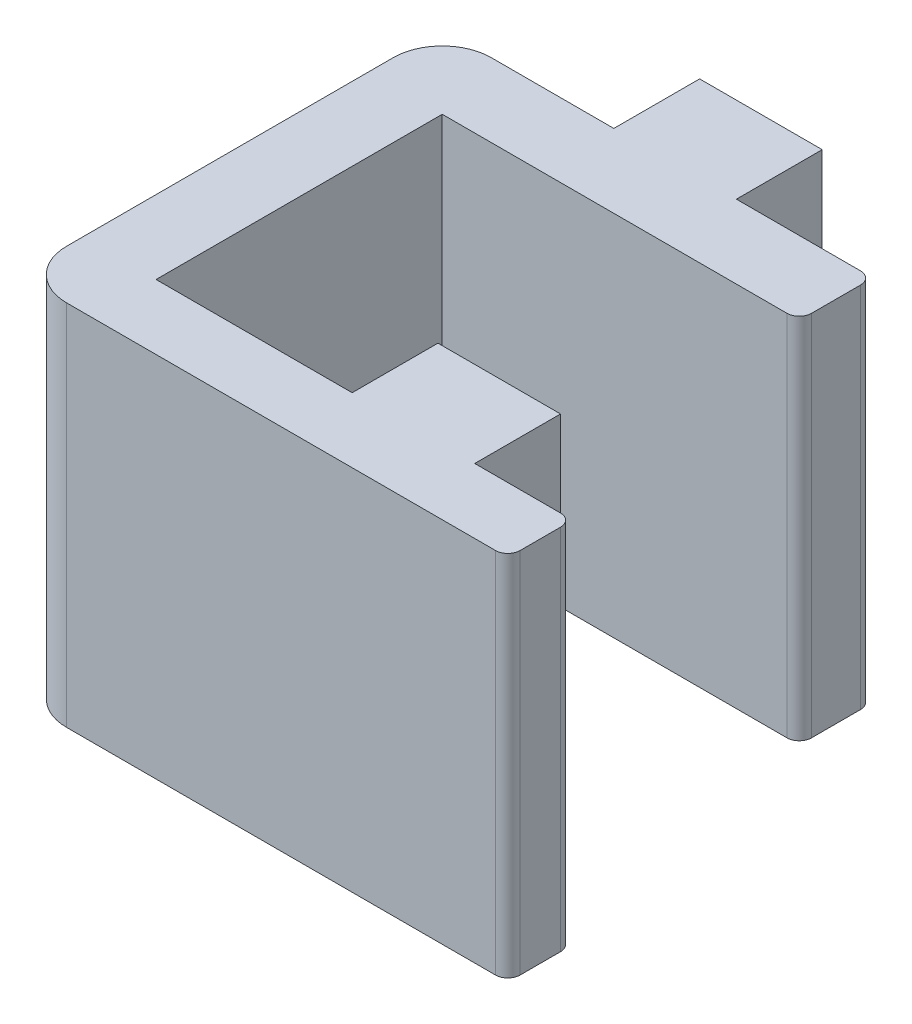
SolidWorks part; units mm, degrees
ref_plane "Front Plane" through (0, 0, 0) normal (0, 0, 1) x (1, 0, 0)
ref_plane "Top Plane" through (0, 0, 0) normal (0, 1, 0) x (1, 0, 0)
ref_plane "Right Plane" through (0, 0, 0) normal (1, 0, 0) x (0, 0, -1)
sketch "Sketch1" plane through (0, 0, 0) normal (0, 1, 0) x (1, 0, 0)
  line L1 (0, 0) -> (-20, 0)
  line L2 (0, 0) -> (0, 2.65)
  line L3 (0, 2.65) -> (-17, 2.65)
  line L6 (-20, 0) -> (-20, 17.325)
  line L8 (-17, 2.65) -> (-17, 14.325)
  line L9 (-20, 17.325) -> (-2.4355, 17.325)
  line L11 (-17, 14.325) -> (-2.4355, 14.325)
  line L12 (-2.4355, 17.325) -> (-2.4355, 14.325)
  dimension "D1" = 2.65
  dimension "D2" = 17.325
  dimension "D3" = 20
  dimension "D4" = 3
  dimension "D5" = 3
extrude "Boss-Extrude1" add sketch "Sketch1" along normal blind 15
sketch "Sketch2" plane through (0, 0, -2.65) normal (0, 0, -1) x (-1, 0, 0)
  line L0 (0, 0) -> (17, 0) construction
  line L1 (9, 0) -> (4, 0)
  line L2 (9, 0) -> (9, 15)
  line L3 (9, 15) -> (4, 15)
  line L4 (4, 0) -> (4, 15)
  line L5 (0, 15) -> (17, 15) construction
  line L6 (17, 15) -> (17, 0) construction
  dimension "D1" = 8
  dimension "D2" = 5
extrude "Boss-Extrude2" add sketch "Sketch2" along normal blind 3.5
sketch "Sketch3" plane through (0, 0, -17.325) normal (0, 0, -1) x (-1, 0, 0)
  line L0 (2.4355, 0) -> (20, 0) construction
  line L1 (13, 0) -> (8, 0)
  line L2 (13, 0) -> (13, 15)
  line L3 (13, 15) -> (8, 15)
  line L4 (8, 0) -> (8, 15)
  line L5 (2.4355, 15) -> (20, 15) construction
  line L6 (20, 15) -> (20, 0) construction
  dimension "D1" = 7
  dimension "D2" = 5
extrude "Boss-Extrude3" add sketch "Sketch3" along normal blind 3.5
fillet "Fillet1" radius 2 2 edges at (-20, 7.5, 0) (-20, 7.5, -17.325)
fillet "Fillet2" radius 0.5 4 edges at (-2.4355, 7.5, -17.325) (-2.4355, 7.5, -14.325) (0, 7.5, 0) (0, 7.5, -2.65)
